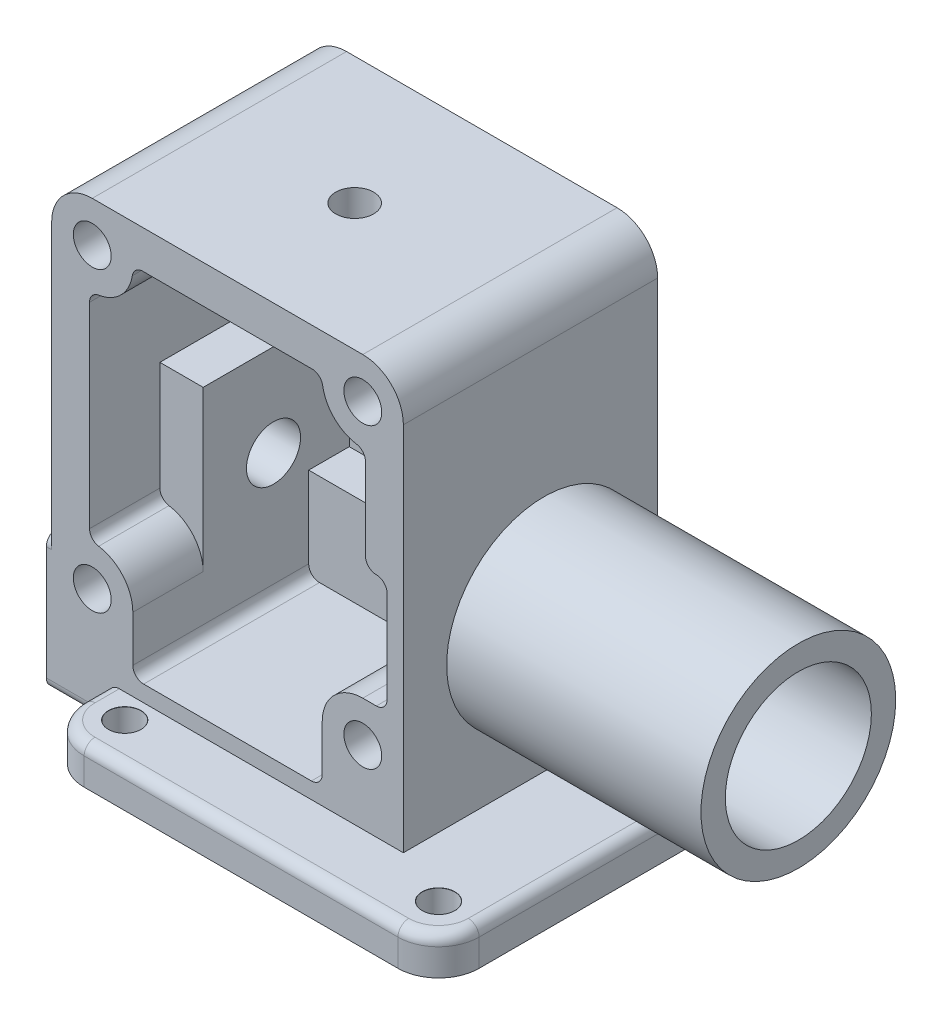
SolidWorks part; units mm, degrees
ref_plane "Front Plane" through (0, 0, 0) normal (0, 0, 1) x (1, 0, 0)
ref_plane "Top Plane" through (0, 0, 0) normal (0, 1, 0) x (1, 0, 0)
ref_plane "Right Plane" through (0, 0, 0) normal (1, 0, 0) x (0, 0, -1)
sketch "Sketch2" plane through (0, 0, 0) normal (0, 1, 0) x (1, 0, 0)
  line L1 (-29, -36.5) -> (29, -36.5)
  line L2 (-36.5, -29) -> (-36.5, 29)
  line L3 (-29, 36.5) -> (29, 36.5)
  line L4 (36.5, -29) -> (36.5, 29)
  line L5 (-36.5, -36.5) -> (36.5, 36.5) construction
  line L6 (-36.5, 36.5) -> (36.5, -36.5) construction
  arc A0 (29, -36.5) -> (36.5, -29) centre (29, -29) ccw
  arc A1 (-29, -36.5) -> (-36.5, -29) centre (-29, -29) cw
  arc A2 (29, 36.5) -> (36.5, 29) centre (29, 29) cw
  arc A3 (-36.5, 29) -> (-29, 36.5) centre (-29, 29) cw
  point P0 (0, 0)
  dimension "D3" = 7.5
  dimension "D1" = 73
  dimension "D2" = 73
extrude "Boss-Extrude1" add sketch "Sketch2" along normal blind 7
hole_wizard "Ø6.0mm Dowel Hole1" positions "3DSketch1" profile "Sketch4" hole size "Ø6.0" standard "ANSI Metric" end condition through all
sketch3d "3DSketch1"
  line L0 (-29, 7, -29) -> (-29, 0, -29) construction
  line L1 (29, 7, -29) -> (29, 0, -29) construction
  line L2 (29, 7, 29) -> (29, 0, 29) construction
  line L3 (-29, 7, 29) -> (-29, 0, 29) construction
  point P0 (-29, 7, -29)
  point P4 (29, 7, -29)
  point P8 (29, 7, 29)
  point P12 (-29, 7, 29)
sketch "Sketch4" plane through (-29, 7, -29) normal (1, 0, 0) x (0, 0, 1)
  line L0 (0, 0) -> (0, 7)
  line L1 (0, 7) -> (3, 7)
  line L2 (3, 7) -> (3, 0.025)
  line L3 (3, 0.025) -> (3.025, 0)
  line L5 (3.025, 0) -> (0, 0)
  line L6 (-3, 0.025) -> (-3.025, 0) construction
  line L11 (0, -6.35) -> (0, 107.95) construction
  dimension "Thru Hole Dia." = 6
  dimension "Thru Hole Depth" = 7
  dimension "Near C'Sink Dia." = 6.05
  dimension "Near C'Sink Angle" = 90
sketch "Sketch5" plane through (0, 7, 0) normal (0, 1, 0) x (1, 0, 0)
  line L1 (18, 22.5) -> (-47, 22.5)
  line L2 (18, 22.5) -> (18, -24.5)
  line L3 (18, -24.5) -> (-47, -24.5)
  line L4 (-47, 22.5) -> (-47, -24.5)
  dimension "D1" = 22.5
  dimension "D2" = 47
  dimension "D3" = 47
  dimension "D4" = 65
extrude "Boss-Extrude2" add sketch "Sketch5" along normal blind 76 and the other way blind 7
fillet "Fillet1" radius 7.5 2 edges at (18, 83, 1) (-47, 83, 1)
hole_wizard "Ø6.0mm Dowel Hole2" positions "3DSketch2" profile "Sketch8" hole size "Ø6.0" standard "ANSI Metric" end condition through all
sketch3d "3DSketch2"
  line L0 (-39.5, 75.5, 24.5) -> (-39.5, 75.5, -22.5) construction
  line L1 (10.5, 75.5, -22.5) -> (10.5, 75.5, 24.5) construction
  line L3 (-39.5, 75.5, 24.5) -> (-39.5, 20.5, 24.5) construction
  line L7 (10.5, 75.5, 24.5) -> (10.5, 20.5, 24.5) construction
  line L9 (-39.5, 75.5, 24.5) -> (10.5, 75.5, 24.5) construction
  line L11 (-47, 0, 24.5) -> (-47, 75.5, 24.5) construction
  point P0 (-39.5, 75.5, 24.5)
  point P4 (10.5, 75.5, 24.5)
  point P8 (-39.5, 20.5, 24.5)
  point P10 (10.5, 20.5, 24.5)
  dimension "D1" = 55
  dimension "D2" = 55
  dimension "D3" = 7.5
sketch "Sketch8" plane through (-39.5, 75.5, 24.5) normal (1, 0, 0) x (0, -1, 0)
  line L0 (0, 0) -> (0, 61)
  line L1 (0, 61) -> (3.5, 61)
  line L2 (3.5, 61) -> (3.5, 0)
  line L5 (3.5, 0) -> (0, 0)
  line L11 (0, -6.35) -> (0, 107.95) construction
  dimension "Thru Hole Dia." = 7
  dimension "Thru Hole Depth" = 61
sketch "Sketch9" plane through (0, 0, 24.5) normal (0, 0, 1) x (1, 0, 0)
  line L0 (11, 66.1192) -> (11, 51)
  line L1 (-32, 20.5) -> (-32, 12)
  line L2 (15, 47) -> (15, 30)
  line L3 (18, 7) -> (18, 75.5) construction
  line L4 (-30, 10) -> (1, 10)
  line L5 (-29, 0) -> (29, 0) construction
  line L6 (-30.1192, 76) -> (1.1192, 76)
  line L8 (-39.5, 83) -> (10.5, 83) construction
  line L9 (3, 20.5) -> (3, 12)
  line L10 (10.5, 28) -> (20.3053, 28) construction
  line L11 (13, 28) -> (10.5, 28)
  line L12 (-40, 29.8808) -> (-40, 66.1192)
  line L14 (-47, 0) -> (-47, 75.5) construction
  arc A0 (3.0941, 74.3158) -> (9.3158, 68.0941) centre (10.5, 75.5) ccw
  arc A1 (-38.3158, 68.0941) -> (-32.0941, 74.3158) centre (-39.5, 75.5) ccw
  arc A2 (-32, 20.5) -> (-38.3158, 27.9059) centre (-39.5, 20.5) ccw
  arc A3 (10.5, 28) -> (3, 20.5) centre (10.5, 20.5) ccw
  arc A4 (1.1192, 76) -> (3.0941, 74.3158) centre (1.1192, 74) cw
  arc A5 (11, 66.1192) -> (9.3158, 68.0941) centre (9, 66.1192) ccw
  arc A6 (13, 49) -> (11, 51) centre (13, 51) cw
  arc A7 (1, 10) -> (3, 12) centre (1, 12) ccw
  arc A8 (13, 49) -> (15, 47) centre (13, 47) cw
  arc A9 (13, 28) -> (15, 30) centre (13, 30) ccw
  arc A10 (-40, 66.1192) -> (-38.3158, 68.0941) centre (-38, 66.1192) cw
  arc A11 (-40, 29.8808) -> (-38.3158, 27.9059) centre (-38, 29.8808) ccw
  arc A12 (-32, 12) -> (-30, 10) centre (-30, 12) ccw
  arc A13 (-32.0941, 74.3158) -> (-30.1192, 76) centre (-30.1192, 74) cw
  point P36 (15, 26.5)
  point P39 (15, 28)
  point P41 (0, 0)
  point P44 (0, 0)
  point P48 (0, 0)
  point P49 (0, 0)
  point P55 (-39.5, 20.5005)
  dimension "D4" = 15
  dimension "D5" = 15
  dimension "D6" = 15
  dimension "D7" = 15
  dimension "D9" = 2
  dimension "D11" = 2
  dimension "D3" = 2
  dimension "D13" = 2
  dimension "D15" = 2
  dimension "D16" = 2
  dimension "D1" = 7
  dimension "D2" = 4
  dimension "D8" = 7
  dimension "D10" = 10
  dimension "D12" = 19
  dimension "D14" = 7
extrude "Cut-Extrude1" cut sketch "Sketch9" against normal blind 40
sketch "Sketch11" plane through (0, 0, -15.5) normal (0, 0, 1) x (1, 0, 0)
  line L0 (-32, 20.5) -> (-32, 50)
  line L1 (-40, 50) -> (-32, 50)
  line L3 (-40, 66.1192) -> (-40, 29.8808) construction
  line L4 (-29, 7) -> (-36.5, 7) construction
  line L5 (-40, 50) -> (-40, 29.8808)
  arc A0 (-32, 20.5) -> (-38.3158, 27.9059) centre (-39.5, 20.5) ccw
  arc A1 (-38.3158, 27.9059) -> (-40, 29.8808) centre (-38, 29.8808) cw
  dimension "D2" = 2
  dimension "D1" = 43
extrude "Boss-Extrude3" add sketch "Sketch11" along normal blind 27
sketch "Sketch12" plane through (0, 0, -15.5) normal (0, 0, 1) x (1, 0, 0)
  line L0 (-9.5, 10) -> (-9.5, 19.5)
  line L1 (-30, 10) -> (1, 10) construction
  line L2 (-17, 27) -> (-32, 27)
  line L3 (-32, 50) -> (-32, 12) construction
  line L4 (-47, 0) -> (-47, 75.5) construction
  line L5 (-29, 0) -> (29, 0) construction
  line L6 (-32, 27) -> (-32, 12)
  line L7 (-9.5, 10) -> (-30, 10)
  arc A0 (-9.5, 19.5) -> (-17, 27) centre (-17, 19.5) ccw
  arc A1 (-30, 10) -> (-32, 12) centre (-30, 12) cw
  dimension "D1" = 7.5
  dimension "D4" = 2
  dimension "D2" = 30
  dimension "D3" = 19.5
extrude "Boss-Extrude4" add sketch "Sketch12" along normal blind 7.5
hole_wizard "Ø6.0mm Dowel Hole3" positions "3DSketch3" profile "Sketch13" hole size "Ø6.0" standard "ANSI Metric" end condition through all
sketch3d "3DSketch3"
  line L0 (-17, 19.5, -8) -> (-17, 19.5, -15.5) construction
  point P0 (-17, 19.5, -8)
sketch "Sketch13" plane through (-17, 19.5, -8) normal (1, 0, 0) x (0, -1, 0)
  line L0 (0, 0) -> (0, 28.5)
  line L1 (0, 28.5) -> (3, 28.5)
  line L2 (3, 28.5) -> (3, 0)
  line L5 (3, 0) -> (0, 0)
  line L11 (0, -6.35) -> (0, 107.95) construction
  dimension "Thru Hole Dia." = 6
  dimension "Thru Hole Depth" = 28.5
sketch "Sketch14" plane through (0, 0, -22.5) normal (0, 0, -1) x (-1, 0, 0)
  line L0 (-29, 0) -> (29, 0) construction
  line L1 (-5.8328, 48) -> (-5.8328, 30)
  line L2 (10.1672, 48) -> (10.1672, 30)
  arc A0 (10.1672, 48) -> (-5.8328, 48) centre (2.1672, 48) ccw
  arc A1 (-5.8328, 30) -> (10.1672, 30) centre (2.1672, 30) ccw
  dimension "D1" = 16
  dimension "D2" = 16
  dimension "D3" = 18
  dimension "D4" = 30
extrude "Cut-Extrude2" cut sketch "Sketch14" against normal blind 14.5
sketch "Sketch15" plane through (-47, 0, 0) normal (-1, 0, 0) x (0, 0, 1)
  line L0 (-22.5, 0) -> (-22.5, 75.5) construction
  line L1 (24.5, 0) -> (-22.5, 0)
  line L2 (24.5, 0) -> (24.5, 23)
  line L3 (22.5, 25) -> (-20.5, 25)
  line L4 (-22.5, 0) -> (-22.5, 23)
  line L5 (-22.5, 0) -> (24.5, 0) construction
  arc A0 (24.5, 23) -> (22.5, 25) centre (22.5, 23) ccw
  arc A1 (-20.5, 25) -> (-22.5, 23) centre (-20.5, 23) ccw
  point P0 (24.5, 0)
  point P3 (-22.5, 0)
  point P11 (-22.5, 25)
  point P14 (24.5, 0)
  point P17 (-20.5, 0)
  point P21 (0, 0)
  dimension "D2" = 2
  dimension "D1" = 25
extrude "Boss-Extrude5" add sketch "Sketch15" along normal blind 1
hole_wizard "Ø5.0mm Dowel Hole1" positions "3DSketch4" profile "Sketch19" hole size "Ø5.0" standard "ANSI Metric"
sketch3d "3DSketch4"
  line L0 (-48, 0, -22.5) -> (-48, 0, 24.5) construction
  line L1 (-48, 23, -22.5) -> (-48, 0, -22.5) construction
  point P0 (-48, 12.5, 18.5)
  point P2 (-48, 12.5, -18.5)
  dimension "D1" = 12.5
  dimension "D2" = 12.5
  dimension "D3" = 4
  dimension "D4" = 37
sketch "Sketch19" plane through (-48, 12.5, 18.5) normal (0, 1, 0) x (0, 0, 1)
  line L0 (0, 0) -> (0, 14.5022)
  line L1 (0, 14.5022) -> (2.5, 13)
  line L2 (2.5, 13) -> (2.5, 0)
  line L5 (2.5, 0) -> (0, 0)
  line L10 (0, 14.5022) -> (-2.5, 13) construction
  line L11 (0, -6.35) -> (0, 107.95) construction
  dimension "Hole Dia." = 5
  dimension "Hole Depth" = 13
  dimension "Drill Angle" = 118
sketch "Sketch21" plane through (0, 0, -22.5) normal (0, 0, -1) x (-1, 0, 0)
  line L0 (48, 0) -> (36.5, 0)
  line L1 (36.5, 0) -> (36.5, 7)
  line L2 (36.5, 7) -> (-18, 7)
  line L3 (-18, 7) -> (-18, 12)
  line L4 (-18, 7) -> (-18, 75.5) construction
  line L5 (-18, 12) -> (48, 12)
  line L6 (48, 23) -> (48, 0) construction
  line L7 (48, 12) -> (48, 0)
  dimension "D1" = 12
extrude "Boss-Extrude6" add sketch "Sketch21" along normal blind 2
sketch "Sketch23" plane through (-48, 0, 0) normal (-1, 0, 0) x (0, 0, 1)
  line L0 (-24.5, 0) -> (24.5, 0) construction
  line L2 (-22.5, 0) -> (-24.5, 0)
  line L4 (-24.5, 0) -> (-24.5, 2)
  line L5 (24.5, 0) -> (22.5, 0)
  line L6 (24.5, 0) -> (24.5, 2)
  arc A0 (-24.5, 2) -> (-22.5, 0) centre (-22.5, 2) ccw
  arc A1 (22.5, 0) -> (24.5, 2) centre (22.5, 2) ccw
  point P10 (-24.5, 0)
  point P19 (24.5, 0)
  dimension "D1" = 2
  dimension "D2" = 2
  dimension "D3" = 2
  dimension "D4" = 2
  dimension "D5" = 2
  dimension "D6" = 2
extrude "Cut-Extrude4" cut sketch "Sketch23" against normal blind 11.5
sketch "Sketch27" plane through (0, 0, 0) normal (0, -1, 0) x (1, 0, 0)
  circle A0 centre (0, 0) radius 9
  point P2 (1.0087, -5.3104)
  point P4 (0, 0)
  point P6 (0, 0)
  point P8 (0, 0)
  dimension "D2" = 18
extrude "Cut-Extrude5" cut sketch "Sketch27" against normal blind 30
sketch "Sketch28" plane through (-47, 0, 0) normal (-1, 0, 0) x (0, 0, 1)
  line L0 (-22.5, 23) -> (-22.5, 75.5) construction
  line L1 (-22.5, 0) -> (22.5, 0) construction
  circle A0 centre (-1.5, 33) radius 5
  dimension "D2" = 10
  dimension "D1" = 21
  dimension "D3" = 33
extrude "Cut-Extrude6" cut sketch "Sketch28" against normal blind 100
sketch "Sketch29" plane through (18, 0, 0) normal (1, 0, 0) x (0, 0, -1)
  circle A0 centre (1.5, 33) radius 18
  dimension "D1" = 36
extrude "Boss-Extrude7" add sketch "Sketch29" along normal blind 47
sketch "Sketch30" plane through (65, 0, 0) normal (1, 0, 0) x (0, 0, -1)
  circle A0 centre (1.5, 33) radius 13.5
  dimension "D1" = 27
extrude "Cut-Extrude7" cut sketch "Sketch30" against normal blind 37
sketch "Sketch31" plane through (28, 0, 0) normal (1, 0, 0) x (0, 0, -1)
  circle A0 centre (1.5, 33) radius 12
  dimension "D1" = 24
extrude "Cut-Extrude8" cut sketch "Sketch31" against normal blind 5
sketch "Sketch32" plane through (23, 0, 0) normal (1, 0, 0) x (0, 0, -1)
  circle A0 centre (1.5, 33) radius 5
  dimension "D1" = 10
extrude "Cut-Extrude9" cut sketch "Sketch32" against normal through all
sketch "Sketch33" plane through (0, 83, 0) normal (0, 1, 0) x (1, 0, 0)
  line L0 (-47, -1) -> (18, -1) construction
  line L1 (-47, -22.5) -> (-47, 20.5) construction
  line L2 (18, 22.5) -> (18, -24.5) construction
  line L3 (-14.5, -1) -> (-14.5, 22.5) construction
  line L4 (10.5, 22.5) -> (-39.5, 22.5) construction
  circle A0 centre (-14.5, -1) radius 3.5
  dimension "D1" = 7
extrude "Cut-Extrude10" cut sketch "Sketch33" against normal blind 10
fillet "Fillet4" radius 2 9 edges at (-36.5, 7, 26.75) (-34.3033, 7, 34.3033) (0, 7, 36.5) (34.3033, 7, 34.3033) (-36.5, 7, -26.75) (-34.3033, 7, -34.3033) (0, 7, -36.5) (34.3033, 7, -34.3033) (36.5, 7, 0)
